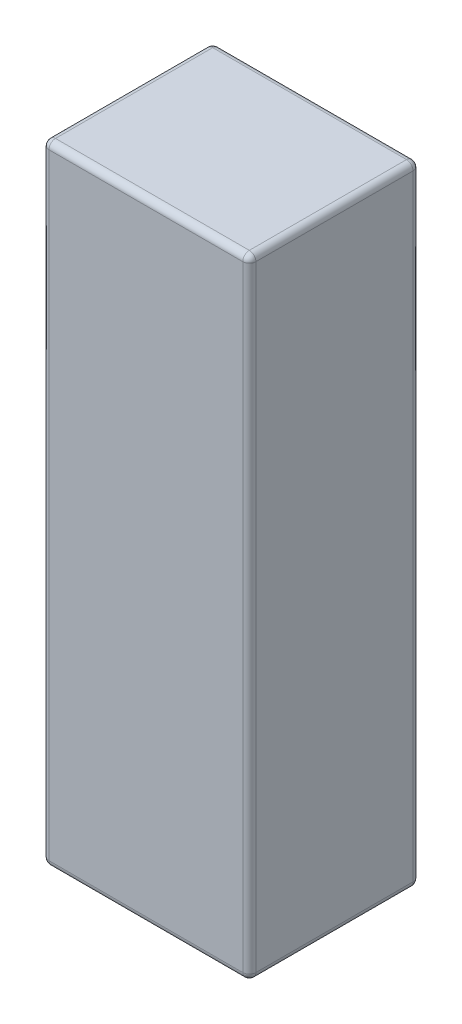
SolidWorks part; units mm, degrees
ref_plane "Ebene vorne" through (0, 0, 0) normal (0, 0, 1) x (1, 0, 0)
ref_plane "Ebene oben" through (0, 0, 0) normal (0, 1, 0) x (1, 0, 0)
ref_plane "Ebene rechts" through (0, 0, 0) normal (1, 0, 0) x (0, 0, -1)
sketch "Skizze1" plane through (0, 0, 0) normal (0, 1, 0) x (1, 0, 0)
  line L0 (0, 6.5) -> (0, -6.5) construction
  line L1 (-7.9, 6.5) -> (7.9, 6.5)
  line L2 (-7.9, 6.5) -> (-7.9, -6.5)
  line L3 (-7.9, -6.5) -> (7.9, -6.5)
  line L4 (7.9, 6.5) -> (7.9, -6.5)
  line L5 (-7.9, 6.5) -> (7.9, -6.5) construction
  line L6 (-7.9, -6.5) -> (7.9, 6.5) construction
  line L7 (-7.9, 0) -> (7.9, 0) construction
  point P0 (0, 0)
  dimension "D1" = 15.8
  dimension "D2" = 13
extrude "Aufsatz-Linear austragen1" add sketch "Skizze1" along normal blind 48
fillet "Verrundung1" radius 0.5 12 edges at (7.9, 48, 0) (0, 48, 6.5) (7.9, 24, 6.5) (0, 0, 6.5) (7.9, 0, 0) (-7.9, 48, 0) (-7.9, 24, 6.5) (-7.9, 0, 0) (7.9, 24, -6.5) (0, 48, -6.5) (-7.9, 24, -6.5) (0, 0, -6.5)
